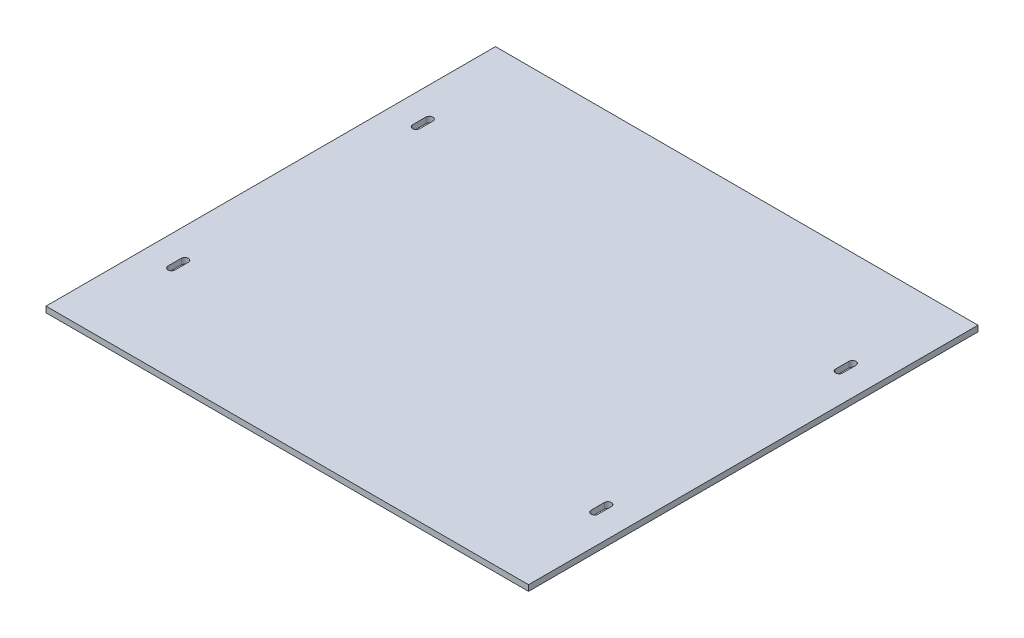
SolidWorks part; units mm, degrees
material "ABS PC"
ref_plane "Front Plane" through (0, 0, 0) normal (0, 0, 1) x (1, 0, 0)
ref_plane "Top Plane" through (0, 0, 0) normal (0, 1, 0) x (1, 0, 0)
ref_plane "Right Plane" through (0, 0, 0) normal (1, 0, 0) x (0, 0, -1)
sketch "Sketch1" plane through (0, 0, 0) normal (0, 1, 0) x (1, 0, 0)
  line L0 (28.575, 339.725) -> (28.575, 327.025) construction
  line L1 (0, 0) -> (463.55, 0)
  line L2 (0, 0) -> (0, 431.8)
  line L3 (0, 431.8) -> (463.55, 431.8)
  line L4 (463.55, 0) -> (463.55, 431.8)
  line L5 (31.9532, 339.725) -> (31.9532, 327.025)
  line L6 (25.1968, 339.725) -> (25.1968, 327.025)
  line L7 (0, 215.9) -> (463.55, 215.9) construction
  line L8 (28.575, 92.075) -> (28.575, 104.775) construction
  line L9 (31.9532, 92.075) -> (31.9532, 104.775)
  line L10 (25.1968, 92.075) -> (25.1968, 104.775)
  line L11 (231.775, 215.9) -> (231.775, 431.8) construction
  line L12 (434.975, 92.075) -> (434.975, 104.775) construction
  line L13 (431.5968, 92.075) -> (431.5968, 104.775)
  line L14 (438.3532, 92.075) -> (438.3532, 104.775)
  line L15 (434.975, 339.725) -> (434.975, 327.025) construction
  line L16 (431.5968, 339.725) -> (431.5968, 327.025)
  line L17 (438.3532, 339.725) -> (438.3532, 327.025)
  arc A0 (31.9532, 339.725) -> (25.1968, 339.725) centre (28.575, 339.725) ccw
  arc A1 (25.1968, 327.025) -> (31.9532, 327.025) centre (28.575, 327.025) ccw
  arc A2 (31.9532, 92.075) -> (25.1968, 92.075) centre (28.575, 92.075) cw
  arc A3 (25.1968, 104.775) -> (31.9532, 104.775) centre (28.575, 104.775) cw
  arc A4 (431.5968, 92.075) -> (438.3532, 92.075) centre (434.975, 92.075) ccw
  arc A5 (438.3532, 104.775) -> (431.5968, 104.775) centre (434.975, 104.775) ccw
  arc A6 (431.5968, 339.725) -> (438.3532, 339.725) centre (434.975, 339.725) cw
  arc A7 (438.3532, 327.025) -> (431.5968, 327.025) centre (434.975, 327.025) cw
  point P7 (28.575, 333.375)
  point P16 (28.575, 98.425)
  point P25 (434.975, 98.425)
  point P32 (434.975, 333.375)
  dimension "D3" = 6.7564
  dimension "D1" = 431.8
  dimension "D2" = 463.55
  dimension "D4" = 12.7
  dimension "D5" = 28.575
  dimension "D6" = 117.475
extrude "Boss-Extrude1" add sketch "Sketch1" along normal blind 5.588
fillet "Fillet1" [suppressed] radius 3.175
sketch "Sketch2" plane through (0, 5.588, 0) normal (0, 1, 0) x (1, 0, 0)
  line L0 (463.55, 431.8) -> (0, 431.8) construction
  line L1 (0, 0) -> (463.55, 0) construction
  circle A0 centre (231.775, 431.8) radius 12.7
  circle A1 centre (231.775, 0) radius 12.7
  dimension "D1" = 25.4
extrude "Cut-Extrude1" [suppressed] cut sketch "Sketch2" against normal through all
fillet "Fillet2" [suppressed] radius 3.175
